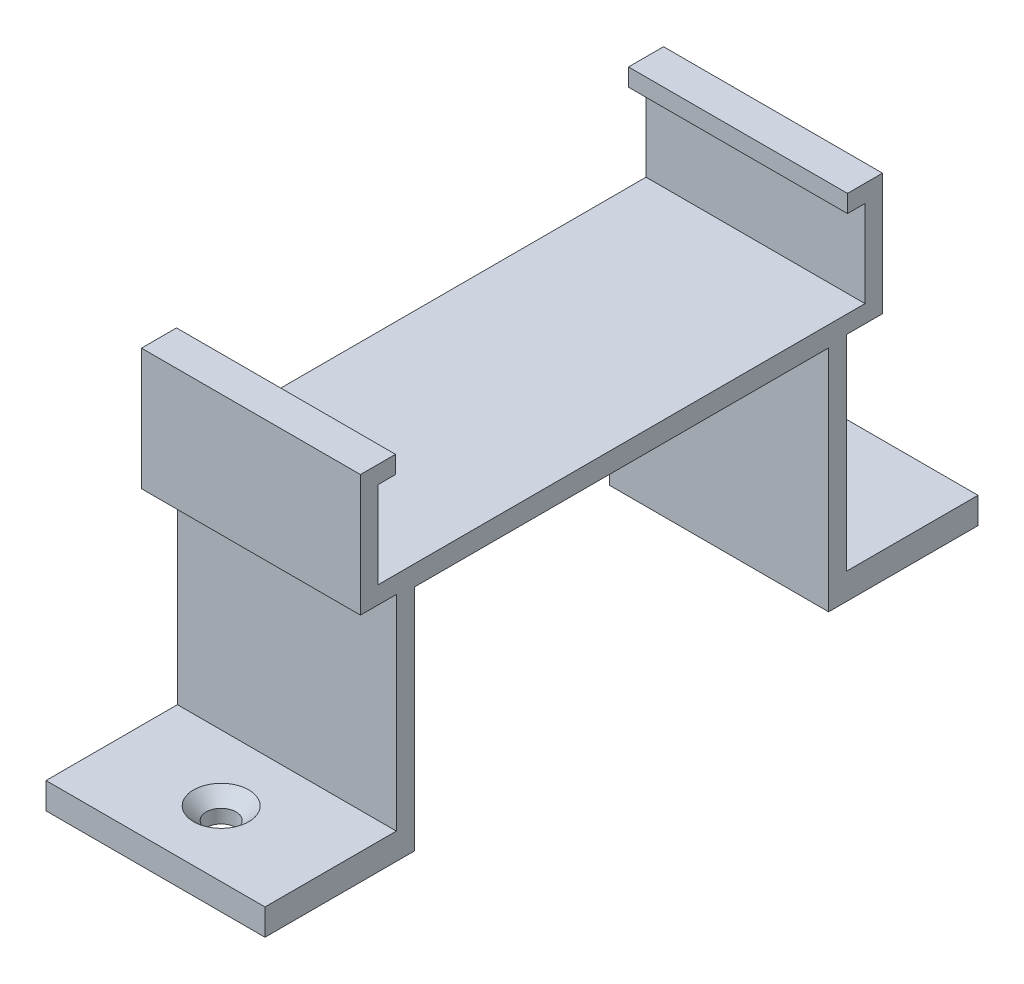
SolidWorks part; units mm, degrees
ref_plane "Front Plane" through (0, 0, 0) normal (0, 0, 1) x (1, 0, 0)
ref_plane "Top Plane" through (0, 0, 0) normal (0, 1, 0) x (1, 0, 0)
ref_plane "Right Plane" through (0, 0, 0) normal (1, 0, 0) x (0, 0, -1)
sketch "Sketch1" plane through (0, 0, 0) normal (0, 1, 0) x (1, 0, 0)
  line L1 (-12.5, -25.7) -> (12.5, -25.7)
  line L2 (-12.5, -25.7) -> (-12.5, 25.7)
  line L3 (-12.5, 25.7) -> (12.5, 25.7)
  line L4 (12.5, -25.7) -> (12.5, 25.7)
  line L5 (-12.5, -25.7) -> (12.5, 25.7) construction
  line L6 (-12.5, 25.7) -> (12.5, -25.7) construction
  point P0 (0, 0)
  dimension "D1" = 25
  dimension "D2" = 51.4
extrude "Boss-Extrude1" add sketch "Sketch1" along normal blind 28.4
sketch "Sketch2" plane through (12.5, 0, 0) normal (1, 0, 0) x (0, 0, -1)
  line L0 (25.7, 28.4) -> (25.7, 0) construction
  line L1 (-23.65, 26.1) -> (23.65, 26.1)
  line L2 (-23.65, 26.1) -> (-23.65, -1)
  line L3 (-23.65, -1) -> (23.65, -1)
  line L4 (23.65, 26.1) -> (23.65, -1)
  line L6 (-25.7, 28.4) -> (-25.7, 0) construction
  line L7 (-25.7, 0) -> (25.7, 0) construction
  dimension "D1" = 2.05
  dimension "D2" = 27.1
  dimension "D3" = 2.05
  dimension "D4" = 1
extrude "Cut-Extrude1" cut sketch "Sketch2" against normal blind 147
sketch "Sketch4" plane through (0, 28.4, 0) normal (0, 1, 0) x (1, 0, 0)
  line L0 (-12.5, 25.7) -> (-12.5, -25.7) construction
  line L1 (12.5, 29.8) -> (-12.5, 29.8)
  line L2 (12.5, 29.8) -> (12.5, -29.8)
  line L3 (12.5, -29.8) -> (-12.5, -29.8)
  line L4 (-12.5, 29.8) -> (-12.5, -29.8)
  line L5 (12.5, -25.7) -> (12.5, 25.7) construction
  line L8 (-12.5, 25.7) -> (-12.5, 29.8) construction
  line L9 (12.5, 25.7) -> (-12.5, 25.7) construction
  line L10 (-12.5, -29.8) -> (-12.5, -25.7) construction
  line L11 (-12.5, -25.7) -> (12.5, -25.7) construction
  dimension "D1" = 59.6
extrude "Boss-Extrude2" add sketch "Sketch4" along normal blind 11.9 and the other way blind 2
sketch "Sketch5" plane through (-12.5, 0, 0) normal (-1, 0, 0) x (0, 0, 1)
  line L0 (-29.8, 40.3) -> (-29.8, 26.4) construction
  line L1 (-27.8, 28.4) -> (27.8, 28.4)
  line L2 (-27.8, 28.4) -> (-27.8, 38.3)
  line L3 (-27.8, 38.3) -> (27.8, 38.3)
  line L4 (27.8, 28.4) -> (27.8, 38.3)
  line L5 (29.8, 40.3) -> (29.8, 26.4) construction
  line L6 (-29.8, 40.3) -> (29.8, 40.3) construction
  dimension "D1" = 2
  dimension "D2" = 2
  dimension "D3" = 2
  dimension "D4" = 9.9
extrude "Cut-Extrude5" cut sketch "Sketch5" against normal through all
sketch "Sketch6" plane through (-12.5, 0, 0) normal (-1, 0, 0) x (0, 0, 1)
  line L0 (27.8, 38.3) -> (-27.8, 38.3) construction
  line L1 (-25.8, 38.3) -> (25.8, 38.3)
  line L2 (-25.8, 38.3) -> (-25.8, 40.3)
  line L3 (-25.8, 40.3) -> (25.8, 40.3)
  line L4 (25.8, 38.3) -> (25.8, 40.3)
  line L5 (-29.8, 40.3) -> (29.8, 40.3) construction
  line L6 (29.8, 40.3) -> (29.8, 26.4) construction
  line L7 (-29.8, 40.3) -> (-29.8, 26.4) construction
  dimension "D1" = 4
  dimension "D2" = 4
extrude "Cut-Extrude6" cut sketch "Sketch6" against normal through all
sketch "Sketch7" plane through (0, 0, -25.7) normal (0, 0, -1) x (-1, 0, 0)
  line L0 (12.5, 26.4) -> (12.5, 0) construction
  line L2 (-12.5, 0) -> (12.5, 0) construction
  line L3 (-12.5, 3) -> (12.5, 3)
  line L4 (-12.5, 3) -> (-12.5, 0)
  line L5 (-12.5, 0) -> (12.5, 0)
  line L6 (12.5, 3) -> (12.5, 0)
  line L7 (-12.5, 26.4) -> (-12.5, 0) construction
  dimension "D1" = 3
extrude "Boss-Extrude3" add sketch "Sketch7" along normal blind 15
sketch "Sketch8" plane through (0, 0, 25.7) normal (0, 0, 1) x (1, 0, 0)
  line L1 (12.5, 26.4) -> (12.5, 0) construction
  line L2 (-12.5, 0) -> (12.5, 0) construction
  line L3 (-12.5, 3) -> (12.5, 3)
  line L4 (-12.5, 3) -> (-12.5, 0)
  line L5 (-12.5, 0) -> (12.5, 0)
  line L6 (12.5, 3) -> (12.5, 0)
  line L7 (-12.5, 26.4) -> (-12.5, 0) construction
  dimension "D1" = 3
extrude "Boss-Extrude4" add sketch "Sketch8" along normal blind 15
sketch "Sketch23" plane through (0, 3, 0) normal (0, 1, 0) x (1, 0, 0)
  line L0 (0, -40.7) -> (0, -25.7) construction
  line L3 (12.5, -40.7) -> (-12.5, -40.7) construction
  line L4 (0, 0) -> (0, 25.7) construction
  line L6 (-12.5, 25.7) -> (12.5, 25.7) construction
  line L8 (12.5, 33.2) -> (0, 33.2) construction
  line L9 (12.5, 40.7) -> (12.5, 25.7) construction
  line L10 (0, 25.7) -> (0, 40.7) construction
  line L11 (-12.5, 40.7) -> (12.5, 40.7) construction
  line L12 (12.5, -25.7) -> (-12.5, -25.7) construction
  line L13 (0, -25.7) -> (0, 0) construction
  line L14 (12.5, -33.2) -> (0, -33.2) construction
  line L15 (12.5, -40.7) -> (12.5, -25.7) construction
  line L16 (-12.5, 25.7) -> (12.5, 25.7) construction
  point P23 (0, -33.2)
  point P24 (0, 33.2)
hole_wizard "CSK for M3 Flat Head Machine Screw4" positions "Sketch23" profile "Sketch24" countersink size "M3" standard "ANSI Metric"
sketch "Sketch24" plane through (0, 3, -33.2) normal (1, 0, 0) x (0, 0, 1)
  line L0 (0, 0) -> (0, 11.4215)
  line L1 (0, 11.4215) -> (1.7, 10.4)
  line L2 (1.7, 10.4) -> (1.7, 1.45)
  line L3 (1.7, 1.45) -> (3.15, 0)
  line L5 (3.15, 0) -> (0, 0)
  line L6 (-1.7, 1.45) -> (-3.15, 0) construction
  line L10 (0, 11.4215) -> (-1.7, 10.4) construction
  line L11 (0, -6.35) -> (0, 107.95) construction
  dimension "Hole Dia." = 3.4
  dimension "Hole Depth" = 10.4
  dimension "Near C'Sink Dia." = 6.3
  dimension "Near C'Sink Angle" = 90
  dimension "Drill Angle" = 118
